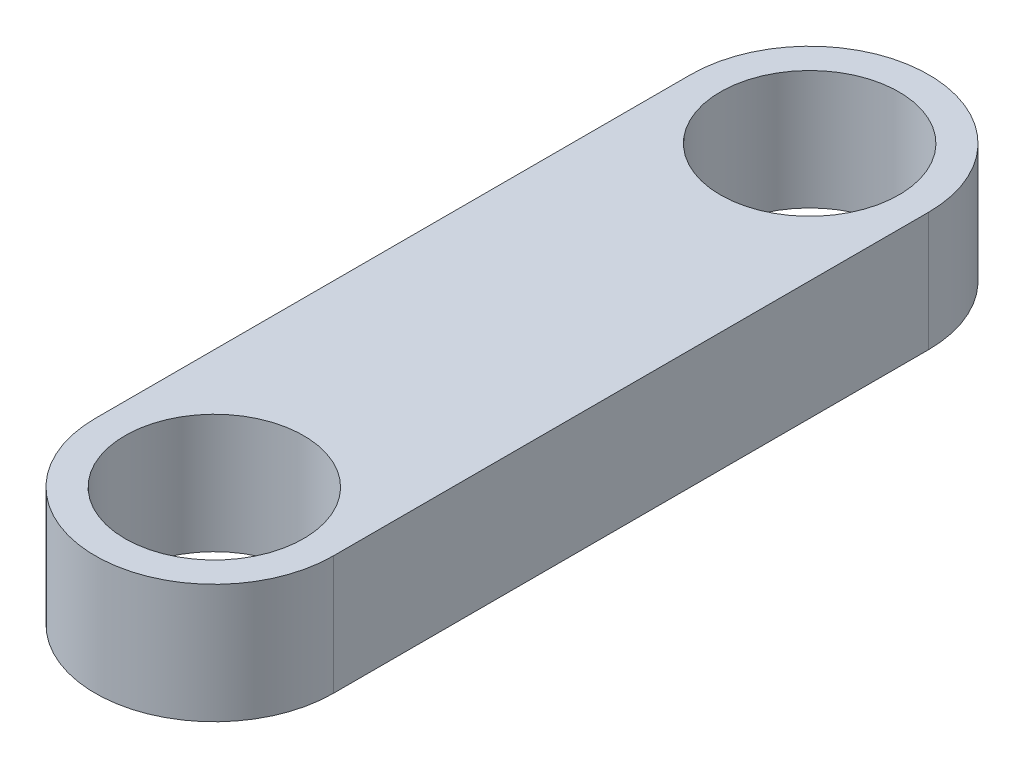
SolidWorks part; units mm, degrees
ref_plane "Front Plane" through (0, 0, 0) normal (0, 0, 1) x (1, 0, 0)
ref_plane "Top Plane" through (0, 0, 0) normal (0, 1, 0) x (1, 0, 0)
ref_plane "Right Plane" through (0, 0, 0) normal (1, 0, 0) x (0, 0, -1)
sketch "Sketch1" plane through (0, 0, 0) normal (0, 1, 0) x (1, 0, 0)
  line L1 (2, -5) -> (-2, -5)
  line L2 (2, -5) -> (2, 5)
  line L3 (2, 5) -> (-2, 5)
  line L4 (-2, -5) -> (-2, 5)
  line L5 (2, -5) -> (-2, 5) construction
  line L6 (2, 5) -> (-2, -5) construction
  circle A0 centre (0, 5) radius 2
  circle A1 centre (0, -5) radius 2
  circle A2 centre (0, 5) radius 1.5
  circle A3 centre (0, -5) radius 1.5
  point P0 (0, 0)
  dimension "D3" = 3
  dimension "D1" = 10
  dimension "D2" = 4
extrude "Boss-Extrude1" add sketch "Sketch1" along normal blind 2 contours A1 L2 A0 L4 | A3 L1 A1 | A3 L1 A1 | A2 L3 A0 | A2 L3 A0
